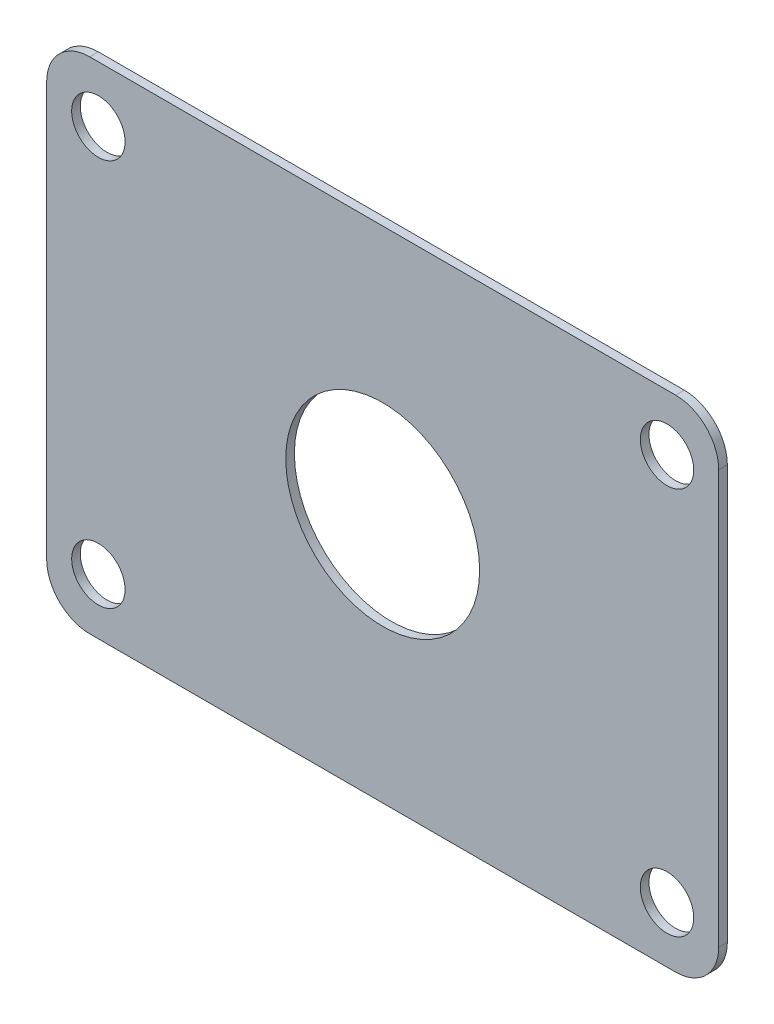
SolidWorks part; units mm, degrees
ref_plane "Front Plane" through (0, 0, 0) normal (0, 0, 1) x (1, 0, 0)
ref_plane "Top Plane" through (0, 0, 0) normal (0, 1, 0) x (1, 0, 0)
ref_plane "Right Plane" through (0, 0, 0) normal (1, 0, 0) x (0, 0, -1)
sketch "Sketch1" plane through (0, 0, 0) normal (0, 0, 1) x (1, 0, 0)
  line L1 (39, 29) -> (-39, 29)
  line L2 (39, 29) -> (39, -29)
  line L3 (39, -29) -> (-39, -29)
  line L4 (-39, 29) -> (-39, -29)
  line L5 (39, 29) -> (-39, -29) construction
  line L6 (39, -29) -> (-39, 29) construction
  point P0 (0, 0)
  dimension "D2" = 78
  dimension "D3" = 58
extrude "Boss-Extrude1" add sketch "Sketch1" along normal blind 1
sketch "Sketch2" plane through (0, 0, 1) normal (0, 0, 1) x (1, 0, 0)
  line L0 (39, 0) -> (-39, 0) construction
  line L1 (39, -29) -> (39, 29) construction
  line L2 (-39, 29) -> (-39, -29) construction
  line L3 (0, 29) -> (0, -29) construction
  line L4 (39, 29) -> (-39, 29) construction
  line L5 (-39, -29) -> (39, -29) construction
  line L7 (-33, -22.5) -> (33, -22.5) construction
  line L8 (-33, -22.5) -> (-33, 22.5) construction
  line L9 (-33, 22.5) -> (33, 22.5) construction
  line L10 (33, -22.5) -> (33, 22.5) construction
  line L11 (-33, -22.5) -> (33, 22.5) construction
  line L12 (-33, 22.5) -> (33, -22.5) construction
  circle A0 centre (-33, 22.5) radius 3.1
  circle A1 centre (33, 22.5) radius 3.1
  circle A2 centre (33, -22.5) radius 3.1
  circle A3 centre (-33, -22.5) radius 3.1
  circle A4 centre (0, 0) radius 11.25
  point P12 (0, 0)
  point P13 (0, 0)
  dimension "D3" = 6.2
  dimension "D4" = 22.5
  dimension "D1" = 66
  dimension "D2" = 45
extrude "Cut-Extrude1" cut sketch "Sketch2" against normal blind 10
fillet "Fillet1" radius 5 4 edges at (-39, -29, 0.5) (39, -29, 0.5) (39, 29, 0.5) (-39, 29, 0.5)
